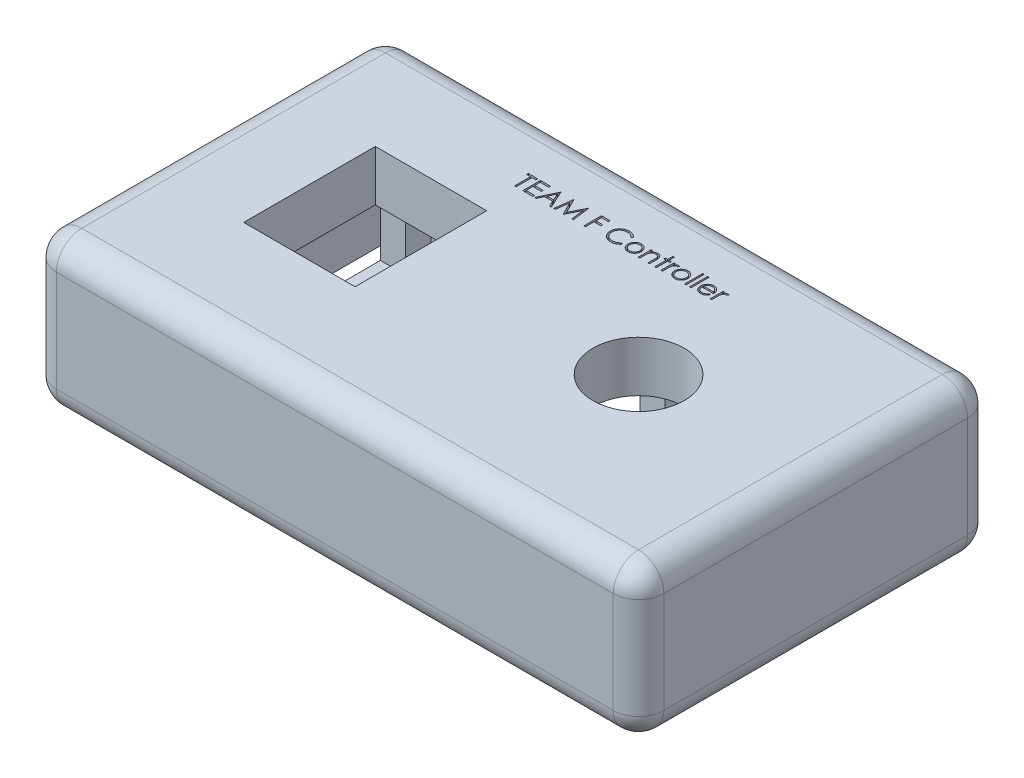
SolidWorks part; units mm, degrees
other "Markup1"
sketch "Sketch10" plane through (-60, 0, -35) normal (0, -1, 0) x (-1, 0, 0)
sketch "Sketch15" plane through (-60, 0, -35) normal (0, -1, 0) x (-1, 0, 0)
sketch "Sketch16" plane through (-60, 0, -35) normal (0, -1, 0) x (-1, 0, 0)
ref_plane "Front Plane" through (0, 0, 0) normal (0, 0, 1) x (1, 0, 0)
ref_plane "Top Plane" through (0, 0, 0) normal (0, 1, 0) x (1, 0, 0)
ref_plane "Right Plane" through (0, 0, 0) normal (1, 0, 0) x (0, 0, -1)
sketch "Sketch1" plane through (0, 0, 0) normal (0, 1, 0) x (1, 0, 0)
  line L1 (-60, 35) -> (60, 35)
  line L2 (-60, 35) -> (-60, -35)
  line L3 (-60, -35) -> (60, -35)
  line L4 (60, 35) -> (60, -35)
  line L5 (-60, 35) -> (60, -35) construction
  line L6 (-60, -35) -> (60, 35) construction
  point P0 (0, 0)
  dimension "D1" = 120
  dimension "D2" = 70
extrude "Boss-Extrude1" add sketch "Sketch1" along normal blind 30
sketch "Sketch2" plane through (0, 30, 0) normal (0, 1, 0) x (1, 0, 0)
  line L1 (-40, 13) -> (-18, 13)
  line L2 (-40, 13) -> (-40, -13)
  line L3 (-40, -13) -> (-18, -13)
  line L4 (-18, 13) -> (-18, -13)
  line L5 (-40, 13) -> (-18, -13) construction
  line L6 (-40, -13) -> (-18, 13) construction
  line L8 (-60, 35) -> (-60, -35) construction
  circle A2 centre (25, 0) radius 9
  point P0 (-29, 0)
  dimension "D1" = 25
  dimension "D2" = 18
  dimension "D4" = 22
  dimension "D5" = 20
  dimension "D3" = 26
extrude "Cut-Extrude1" cut sketch "Sketch2" against normal through all
sketch "Sketch4" plane through (0, 0, -35) normal (0, 0, -1) x (-1, 0, 0)
  line L0 (-60, 30) -> (60, 30) construction
  line L1 (-50, 21.5) -> (-29, 21.5)
  line L2 (-50, 21.5) -> (-50, 8.5)
  line L3 (-50, 8.5) -> (-29, 8.5)
  line L4 (-29, 21.5) -> (-29, 8.5)
  line L5 (-60, 30) -> (-60, 0) construction
  line L6 (0, 0) -> (0, 30) construction
  line L7 (29, 21.5) -> (29, 8.5)
  line L8 (50, 8.5) -> (29, 8.5)
  line L9 (50, 21.5) -> (50, 8.5)
  line L10 (50, 21.5) -> (29, 21.5)
  dimension "D1" = 13
  dimension "D2" = 21
  dimension "D3" = 8.5
  dimension "D4" = 10
extrude "Cut-Extrude3" cut sketch "Sketch4" against normal blind 10
sketch "Sketch6" plane through (0, 0, 0) normal (0, -1, 0) x (1, 0, 0)
  line L0 (-60, -35) -> (-60, 35) construction
  line L1 (-52.5, -27.5) -> (52.5, -27.5)
  line L2 (-52.5, -27.5) -> (-52.5, 27.5)
  line L3 (-52.5, 27.5) -> (52.5, 27.5)
  line L4 (52.5, -27.5) -> (52.5, 27.5)
  line L5 (-52.5, -27.5) -> (52.5, 27.5) construction
  line L6 (-52.5, 27.5) -> (52.5, -27.5) construction
  line L7 (-60, 35) -> (60, 35) construction
  point P0 (0, 0)
  dimension "D1" = 7.5
  dimension "D2" = 7.5
extrude "Cut-Extrude4" cut sketch "Sketch6" against normal blind 20
sketch "Sketch8" plane through (0, 20, 0) normal (0, -1, 0) x (1, 0, 0)
  line L0 (25, 0) -> (25, -9) construction
  line L1 (35, -15.25) -> (30, -15.25)
  line L2 (35, -15.25) -> (35, -10.25)
  line L3 (35, -10.25) -> (30, -10.25)
  line L4 (30, -15.25) -> (30, -10.25)
  line L5 (35, -15.25) -> (30, -10.25) construction
  line L6 (35, -10.25) -> (30, -15.25) construction
  line L7 (35, 9.75) -> (30, 9.75)
  line L8 (35, 9.75) -> (35, 14.75)
  line L9 (35, 14.75) -> (30, 14.75)
  line L10 (30, 9.75) -> (30, 14.75)
  line L11 (35, 9.75) -> (30, 14.75) construction
  line L12 (35, 14.75) -> (30, 9.75) construction
  line L13 (20, 9.75) -> (20, 14.75)
  line L14 (15, 14.75) -> (20, 14.75)
  line L15 (15, 9.75) -> (15, 14.75)
  line L16 (15, 9.75) -> (20, 9.75)
  line L17 (15, -10.25) -> (20, -10.25)
  line L18 (15, -15.25) -> (15, -10.25)
  line L19 (15, -15.25) -> (20, -15.25)
  line L20 (20, -15.25) -> (20, -10.25)
  line L21 (-29, 0) -> (-29, -13) construction
  line L22 (-40, 13) -> (-18, -13) construction
  line L23 (-40, -13) -> (-18, -13) construction
  line L24 (-40, 13) -> (-18, 13) construction
  line L25 (-18, -19) -> (-23, -19)
  line L26 (-18, -19) -> (-18, -14)
  line L27 (-18, -14) -> (-23, -14)
  line L28 (-23, -19) -> (-23, -14)
  line L29 (-18, -19) -> (-23, -14) construction
  line L30 (-18, -14) -> (-23, -19) construction
  line L31 (-18, 14) -> (-23, 14)
  line L32 (-18, 14) -> (-18, 19)
  line L33 (-18, 19) -> (-23, 19)
  line L34 (-23, 14) -> (-23, 19)
  line L35 (-18, 14) -> (-23, 19) construction
  line L36 (-18, 19) -> (-23, 14) construction
  line L37 (-18, -13) -> (-18, 13) construction
  line L38 (-35, 14) -> (-35, 19)
  line L39 (-40, 19) -> (-35, 19)
  line L40 (-40, 14) -> (-40, 19)
  line L41 (-40, 14) -> (-35, 14)
  line L42 (-35, -19) -> (-35, -14)
  line L43 (-40, -14) -> (-35, -14)
  line L44 (-40, -19) -> (-40, -14)
  line L45 (-40, -19) -> (-35, -19)
  circle A0 centre (25, 0) radius 9 construction
  point P0 (32.5, -12.75)
  point P5 (32.5, 12.25)
  point P12 (-20.5, -16.5)
  point P20 (-20.5, 16.5)
extrude "Boss-Extrude2" add sketch "Sketch8" along normal blind 10
ref_plane "Plane1" through (0, 10, 0) normal (0, -1, 0) x (-1, 0, 0)
sketch "Sketch9" plane through (0, 10, 0) normal (0, -1, 0) x (-1, 0, 0)
  line L1 (-35, 15.25) -> (-15, 15.25)
  line L2 (-35, 15.25) -> (-35, -14.75)
  line L3 (-35, -14.75) -> (-15, -14.75)
  line L4 (-15, 15.25) -> (-15, -14.75)
  line L5 (18, 19) -> (40, 19)
  line L6 (18, 19) -> (18, -19)
  line L7 (18, -19) -> (40, -19)
  line L8 (40, 19) -> (40, -19)
extrude "Boss-Extrude3" add sketch "Sketch9" along normal blind 2.5
sketch "Sketch11" plane through (0, 0, -27.5) normal (0, 0, 1) x (1, 0, 0)
  line L0 (-29, 20) -> (29, 20) construction
  line L1 (-29, 8.5) -> (-19, 8.5)
  line L2 (-29, 8.5) -> (-29, 20)
  line L3 (-29, 20) -> (-19, 20)
  line L4 (-19, 8.5) -> (-19, 20)
  line L6 (29, 20) -> (19, 20)
  line L7 (29, 20) -> (29, 8.5)
  line L8 (29, 8.5) -> (19, 8.5)
  line L9 (19, 20) -> (19, 8.5)
extrude "Cut-Extrude5" cut sketch "Sketch11" against normal blind 5
sketch "Sketch12" plane through (0, 30, 0) normal (0, 1, 0) x (1, 0, 0)
  line L0 (-25, 20) -> (25, 20) construction
  line L1 (60, 35) -> (-60, 35) construction
  text T0 "TEAM F Controller\r\n"
  dimension "D1" = 50
  dimension "D2" = 25
  dimension "D3" = 15
extrude "Cut-Extrude6" cut sketch "Sketch12" against normal blind 1
fillet "Fillet1" radius 5 12 edges at (0, 0, -35) (-60, 0, 0) (60, 0, 0) (0, 0, 35) (0, 30, 35) (60, 30, 0) (0, 30, -35) (-60, 30, 0) (-60, 15, 35) (60, 15, 35) (60, 15, -35) (-60, 15, -35)
sketch "Sketch14" plane through (0, 0, -35) normal (0, 0, -1) x (-1, 0, 0)
  line L0 (-55, 30) -> (55, 30) construction
  line L1 (-7.5, 18.75) -> (7.5, 18.75)
  line L2 (-7.5, 18.75) -> (-7.5, 11.25)
  line L3 (-7.5, 11.25) -> (7.5, 11.25)
  line L4 (7.5, 18.75) -> (7.5, 11.25)
  line L5 (-7.5, 18.75) -> (7.5, 11.25) construction
  line L6 (-7.5, 11.25) -> (7.5, 18.75) construction
  point P0 (0, 15)
  dimension "D1" = 15
  dimension "D2" = 7.5
  dimension "D3" = 15
extrude "Cut-Extrude7" cut sketch "Sketch14" against normal up to next
fillet "Fillet2" radius 2 4 edges at (-7.5, 11.25, -31.25) (7.5, 11.25, -31.25) (7.5, 18.75, -31.25) (-7.5, 18.75, -31.25)
equation "\"D8@Sketch8\"=\"D1@Sketch8\""
equation "\"D9@Sketch8\"=\"D2@Sketch8\""
equation "\"D2@Sketch11\"=\"D1@Sketch11\""
